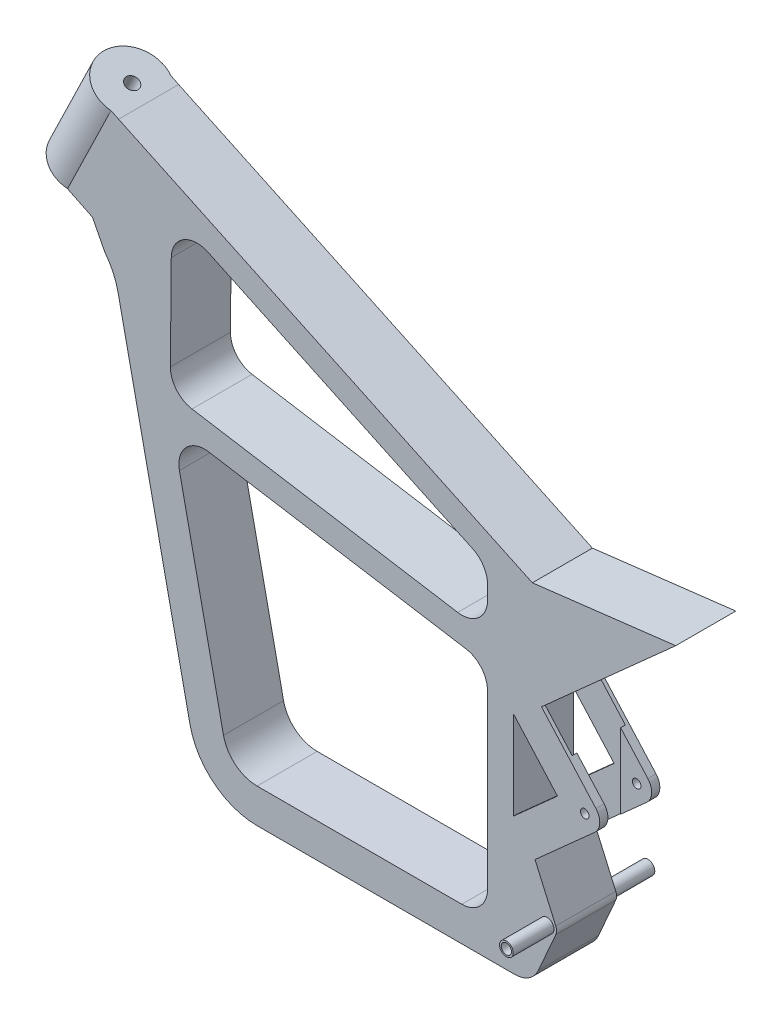
SolidWorks part; units mm, degrees
ref_plane "Спереди" through (0, 0, 0) normal (0, 0, 1) x (1, 0, 0)
ref_plane "Сверху" through (0, 0, 0) normal (0, 1, 0) x (1, 0, 0)
ref_plane "Справа" through (0, 0, 0) normal (1, 0, 0) x (0, 0, -1)
sketch "Эскиз1" plane through (0, 0, 0) normal (0, 0, 1) x (1, 0, 0)
  line B0 (46.4858, 163.526) -> (-16.9694, 234.5062)
  line B1 (-0.3527, 21.5708) -> (-24.5321, 76.5637)
  line B2 (45.1026, 138.8159) -> (-24.5321, 76.5637)
  line B3 (1.6691, 153.6409) -> (-49.8813, 211.3046)
  line B4 (-509.8817, 581.1278) -> (-518.7211, 585.4249)
  line B5 (-424.3418, 331.4105) -> (-130.5583, 283.5194)
  line B6 (-130.5583, 283.5194) -> (-114.708, 280.9355)
  line B7 (-405.7416, 499.0065) -> (-106.5211, 358.3035)
  line B8 (-563.9682, 466.1068) -> (-554.6708, 461.7349)
  line B9 (-510.4616, 405.9724) -> (-426.7399, 12.0927)
  line B10 (-348.4881, -51.2744) -> (-48.0694, -51.2744)
  line B11 (-438.9616, 261.9808) -> (-387.614, 20.4091)
  line B12 (-0.3527, 12.7159) -> (-20.6067, -33.3492)
  line B13 (-49.8813, 107.5557) -> (1.6691, 153.6409)
  line B14 (-348.4881, -11.2744) -> (-109.8813, -11.2744)
  line B15 (-49.8813, 211.3046) -> (-49.8813, 107.5557)
  line B16 (-79.8813, 219.3567) -> (-79.8813, 18.7256)
  line B17 (-105.0546, 248.9659) -> (-404.7905, 297.8273)
  line B18 (-509.8817, 581.1278) -> (-27.5985, 354.3428)
  line B19 (-79.8813, 310.5447) -> (-79.8813, 326.7323)
  line B20 (-27.5985, 354.3428) -> (139.4919, 374.3799)
  line B21 (-16.9694, 234.5062) -> (139.4919, 374.3799)
  line B22 (-518.7211, 585.4249) -> (-574.3524, 470.9898)
  line B23 (-574.3524, 470.9898) -> (-563.9682, 466.1068)
  line B24 (-448.5063, 472.1309) -> (-449.5139, 361.2923)
  line B25 (-106.5211, 358.3035) -> (-97.1153, 353.8806)
  circle B26 centre (33.4391, 151.8625) radius 5
  circle B27 centre (-10.4224, 17.1434) radius 8
  arc B28 (-0.3527, 12.7159) -> (-0.3527, 21.5708) centre (-10.4224, 17.1434) ccw
  arc B29 (-348.4881, -51.2744) -> (-426.7399, 12.0927) centre (-348.4881, 28.7256) cw
  arc B30 (-510.4616, 405.9724) -> (-554.6708, 461.7349) centre (-588.7134, 389.3394) ccw
  arc B31 (-387.614, 20.4091) -> (-348.4881, -11.2744) centre (-348.4881, 28.7256) ccw
  arc B32 (45.1026, 138.8159) -> (46.4858, 163.526) centre (33.4391, 151.8625) ccw
  arc B33 (-448.5063, 472.1309) -> (-405.7416, 499.0065) centre (-418.5076, 471.8582) cw
  arc B34 (-424.3418, 331.4105) -> (-449.5139, 361.2923) centre (-419.5151, 361.0196) cw
  arc B35 (-438.9616, 261.9808) -> (-404.7905, 297.8273) centre (-409.6172, 268.2181) cw
  arc B36 (-114.708, 280.9355) -> (-79.8813, 310.5447) centre (-109.8813, 310.5447) ccw
  arc B37 (-97.1153, 353.8806) -> (-79.8813, 326.7323) centre (-109.8813, 326.7323) cw
  arc B38 (-109.8813, -11.2744) -> (-79.8813, 18.7256) centre (-109.8813, 18.7256) ccw
  arc B39 (-79.8813, 219.3567) -> (-105.0546, 248.9659) centre (-109.8813, 219.3567) ccw
  arc B40 (-48.0694, -51.2744) -> (-20.6067, -33.3492) centre (-48.0694, -21.2744) ccw
sketch_block_instance "Блок-Эскиз3-1"
sketch_block "Блок-Эскиз3" parameters "D1"=16, "D2"=10, "D3"=22, "D4"=80, "D5"=80, "D9"=40, "D14"=30, "D15"=30, "D16"=30, "D17"=30, "D18"=30, "D6"=40, "D7"=40, "D8"=40, "D10"=40, "D11"=30, "D12"=30, "D13"=30
extrude "Бобышка-Вытянуть1" add sketch "Эскиз1" along normal mid plane 70
sketch "Эскиз2" plane through (0, 0, 0) normal (0, 0, 1) x (1, 0, 0)
  circle A0 centre (-10.4224, 17.1434) radius 8
  circle A1 centre (-10.4224, 17.1434) radius 6
  dimension "D1" = 12
extrude "Бобышка-Вытянуть2" add sketch "Эскиз2" along normal mid plane 165
sketch "Эскиз3" plane through (0, 0, 0) normal (0, 0, 1) x (1, 0, 0)
  line L1 (14.7582, 209.7143) -> (57.0602, 209.7143)
  line L2 (14.7582, 209.7143) -> (14.7582, 94.8525)
  line L3 (14.7582, 94.8525) -> (57.0602, 94.8525)
  line L4 (57.0602, 209.7143) -> (57.0602, 94.8525)
extrude "Вырез-Вытянуть1" cut sketch "Эскиз3" against normal mid plane 51
sketch "Эскиз4" plane through (0, 0, 0) normal (0, 0, 1) x (1, 0, 0)
  line L0 (-52.1719, 234.5062) -> (25.275, 234.5062) construction
  line L1 (-49.8813, 211.3046) -> (-49.8813, 73.8119) construction
  line L2 (-49.8813, 76.5637) -> (31.2021, 76.5637) construction
  line L3 (14.7582, 234.5062) -> (14.7582, 76.5637) construction
  line L4 (14.7582, 234.5062) -> (-49.8813, 234.5062)
  line L5 (-49.8813, 234.5062) -> (-49.8813, 76.5637)
  line L6 (-49.8813, 76.5637) -> (14.7582, 76.5637)
  line L7 (14.7582, 76.5637) -> (14.7582, 234.5062)
extrude "Вырез-Вытянуть2" cut sketch "Эскиз4" against normal mid plane 62
sketch "Эскиз5" plane through (131.0393, 269.5517, 0) normal (0.4372, 0.8994, 0) x (0.8994, -0.4372, 0)
  line L0 (-722.4711, 0) -> (-726.4711, 0) construction
  line L1 (-722.4711, -35) -> (-722.4711, 35) construction
  line L2 (-726.4711, 0) -> (-733.9711, 0) construction
  circle A0 centre (-733.9711, 0) radius 7.5
  circle A1 centre (-733.9711, 0) radius 36.8409
  dimension "D1" = 4
  dimension "D2" = 7.5
extrude "Бобышка-Вытянуть3" add sketch "Эскиз5" against normal blind 128.2
sketch "Эскиз6" plane through (0, 0, 0) normal (0, 0, 1) x (1, 0, 0)
  line L0 (-612.9001, 502.2622) -> (-540.3282, 466.9823)
  line L1 (-562.1969, 606.5601) -> (-618.2475, 491.2624) construction
  line L2 (-540.3282, 466.9823) -> (-526.0247, 439.0398)
  line L3 (-526.0247, 439.0398) -> (-623.2761, 486.3174)
  line L4 (-623.2761, 486.3174) -> (-615.5247, 502.2622)
  line L5 (-615.5247, 502.2622) -> (-612.9001, 502.2622)
  arc A0 (-510.4616, 405.9724) -> (-554.6708, 461.7349) centre (-588.7134, 389.3394) ccw construction
extrude "Вырез-Вытянуть3" cut sketch "Эскиз6" against normal mid plane 128
